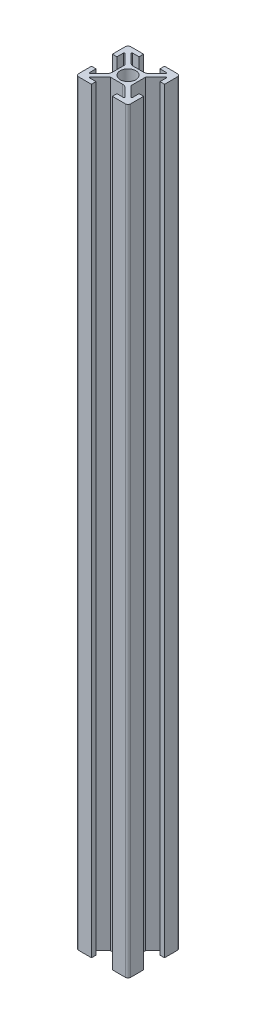
SolidWorks part; units mm, degrees
material "6063-T5"
ref_plane "Plano frontal" through (0, 0, 0) normal (0, 0, 1) x (1, 0, 0)
ref_plane "Plano superior" through (0, 0, 0) normal (0, 1, 0) x (1, 0, 0)
ref_plane "Plano direito" through (0, 0, 0) normal (1, 0, 0) x (0, 0, -1)
sketch "Esboço1" plane through (0, 0, 0) normal (0, 1, 0) x (1, 0, 0)
  line L1 (-10, 10) -> (10, 10)
  line L2 (-10, 10) -> (-10, -10)
  line L3 (-10, -10) -> (10, -10)
  line L4 (10, 10) -> (10, -10)
  line L5 (-10, 10) -> (10, -10) construction
  line L6 (-10, -10) -> (10, 10) construction
  circle A0 centre (0, 0) radius 3
  dimension "D1" = 6
  dimension "D2" = 20
  dimension "D3" = 20
extrude "Ressalto-extrusão1" add sketch "Esboço1" along normal mid plane 290
sketch "Esboço2" plane through (0, 145, 0) normal (0, 1, 0) x (1, 0, 0)
  line L0 (10, 10) -> (-10, 10) construction
  line L1 (-4, 4) -> (4, 4)
  line L2 (-4, 4) -> (-4, -4)
  line L3 (-4, -4) -> (4, -4)
  line L4 (4, 4) -> (4, -4)
  line L5 (-4, 4) -> (4, -4) construction
  line L6 (-4, -4) -> (4, 4) construction
  line L7 (0, 10) -> (0, -10) construction
  line L8 (-10, -10) -> (10, -10) construction
  line L9 (-4, 10) -> (4, 10)
  line L10 (-4, 10) -> (-4, 8.25)
  line L11 (4, 10) -> (4, 8.25)
  line L12 (-4, 8.25) -> (4, 8.25)
  line L13 (-7.05, 8.25) -> (7.05, 8.25)
  line L14 (-7.05, 8.25) -> (-2.8, 4)
  line L15 (7.05, 8.25) -> (2.8, 4)
  line L16 (2.8, 4) -> (-2.8, 4)
  point P0 (0, 0)
  point P19 (0, 8.25)
  line M7 (10, 10) -> (-10, 10)
  dimension "D1" = 8
  dimension "D2" = 8
  dimension "D3" = 1.75
  dimension "D4" = 8
  dimension "D5" = 14.1
  dimension "D6" = 45
  dimension "D7" = 45
extrude "Corte-extrusão1" cut sketch "Esboço2" against normal through all contours L15 L13 L12 L14 L1 | L10 L12 L11 M7
pattern_circular "PadrãoCircular2" count 4 over 360 about axis through (0, 0, 0) along (0, 1, 0) of "Corte-extrusão1"
fillet "Filete2" radius 1 4 edges at (10, 0, 10) (-10, 0, 10) (-10, 0, -10) (10, 0, -10)
fillet "Filete3" radius 2 4 edges at (2.8, 0, 4) (-4, 0, 2.8) (2.8, 0, -4) (-2.8, 0, -4)
fillet "Filete4" radius 0.25 8 edges at (8.25, 0, 7.05) (7.05, 0, 8.25) (-8.25, 0, 7.05) (-7.05, 0, 8.25) (8.25, 0, -7.05) (7.05, 0, -8.25) (-8.25, 0, -7.05) (-7.05, 0, -8.25)
